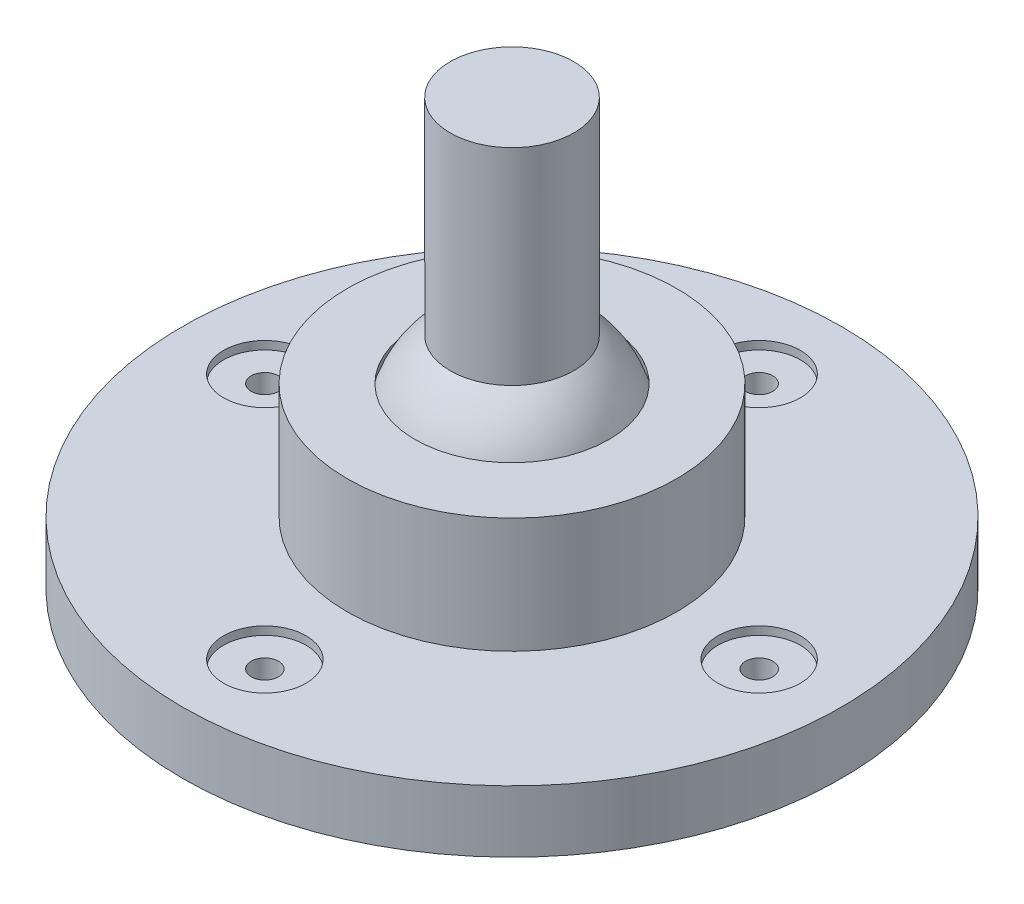
SolidWorks part; units mm, degrees
ref_plane "Front Plane" through (0, 0, 0) normal (0, 0, 1) x (1, 0, 0)
ref_plane "Top Plane" through (0, 0, 0) normal (0, 1, 0) x (1, 0, 0)
ref_plane "Right Plane" through (0, 0, 0) normal (1, 0, 0) x (0, 0, -1)
sketch "Sketch1" plane through (0, 0, 0) normal (0, 0, 1) x (1, 0, 0)
  line L1 (0, 70) -> (15, 70)
  line L2 (-15, 70) -> (-15, 20) construction
  line L4 (15, 70) -> (15, 20)
  line L7 (-15.5, 70.5) -> (15.5, 70.5) construction
  line L8 (-15.5, 70.5) -> (-15.5, 20.2485) construction
  line L9 (15.5, 70.5) -> (15.5, 20.2485) construction
  line L10 (23.5385, 9.8077) -> (40, 9.8077)
  line L11 (0, -33.1923) -> (80, -33.1923)
  line L12 (-49.5385, -33.1923) -> (-49.5385, 9.8077) construction
  line L13 (-49.5385, 9.8077) -> (-23.5385, 9.8077) construction
  line L14 (80, -33.1923) -> (80, -18.1923)
  line L15 (0, 0) -> (0, -50000) construction
  line L16 (0, 70) -> (0, -25)
  line L17 (0, -25.5) -> (0, -33.1923)
  line L18 (-49.5385, -33.1923) -> (0, -33.1923) construction
  line L19 (-15, 70) -> (0, 70) construction
  line L20 (-15, 70) -> (15, 70) construction
  line L21 (40, 9.8077) -> (80, 9.8077) construction
  line L22 (80, 9.8077) -> (40, 9.8077) construction
  line L23 (80, 9.8077) -> (80, -18.1923) construction
  line L24 (80, -18.1923) -> (40, -18.1923)
  line L25 (40, 9.8077) -> (40, -18.1923)
  line L26 (80, -18.1923) -> (80, 9.8077) construction
  arc A0 (0, -25) -> (15, 20) centre (0, 0) ccw
  arc A1 (0, -25.5) -> (23.5385, 9.8077) centre (0, 0) ccw
  arc A2 (-15.5, 20.2485) -> (15.5, 20.2485) centre (0, 0) ccw construction
  arc A3 (-23.5385, 9.8077) -> (0, -25.5) centre (0, 0) ccw construction
  arc A4 (-15, 20) -> (0, -25) centre (0, 0) ccw construction
  arc A5 (-15, 20) -> (15, 20) centre (0, 0) ccw construction
  dimension "D1" = 50
  dimension "D2" = 50
  dimension "D3" = 30
  dimension "D5" = 80
  dimension "D6" = 40
  dimension "D7" = 15
  dimension "D4" = 0.5
revolve "Revolve2" add sketch "Sketch1" angle 360 about L15
sketch "Sketch2" plane through (0, -18.1923, 0) normal (0, 1, 0) x (1, 0, 0)
  circle A0 centre (0, 60) radius 10
  circle A1 centre (0, 0) radius 80 construction
  circle A2 centre (60, 0) radius 10
  circle A3 centre (0, -60) radius 10
  circle A4 centre (-60, 0) radius 10
  dimension "D1" = 20
  dimension "D3" = 4
  dimension "D2" = 60
extrude "Cut-Extrude1" cut sketch "Sketch2" against normal blind 2
sketch "Sketch3" plane through (0, -18.1923, 0) normal (0, 1, 0) x (1, 0, 0)
  circle A0 centre (0, 60) radius 3.302
  circle A1 centre (60, 0) radius 3.302
  circle A2 centre (0, -60) radius 3.302
  circle A3 centre (-60, 0) radius 3.302
  dimension "D1" = 6.604
  dimension "D2" = 4
extrude "Cut-Extrude2" cut sketch "Sketch3" against normal through all
sketch "Sketch4" plane through (0, -33.1923, 0) normal (0, -1, 0) x (1, 0, 0)
  circle A0 centre (0, 0) radius 12.5
  dimension "D1" = 25
extrude "Cut-Extrude3" cut sketch "Sketch4" against normal up to next
